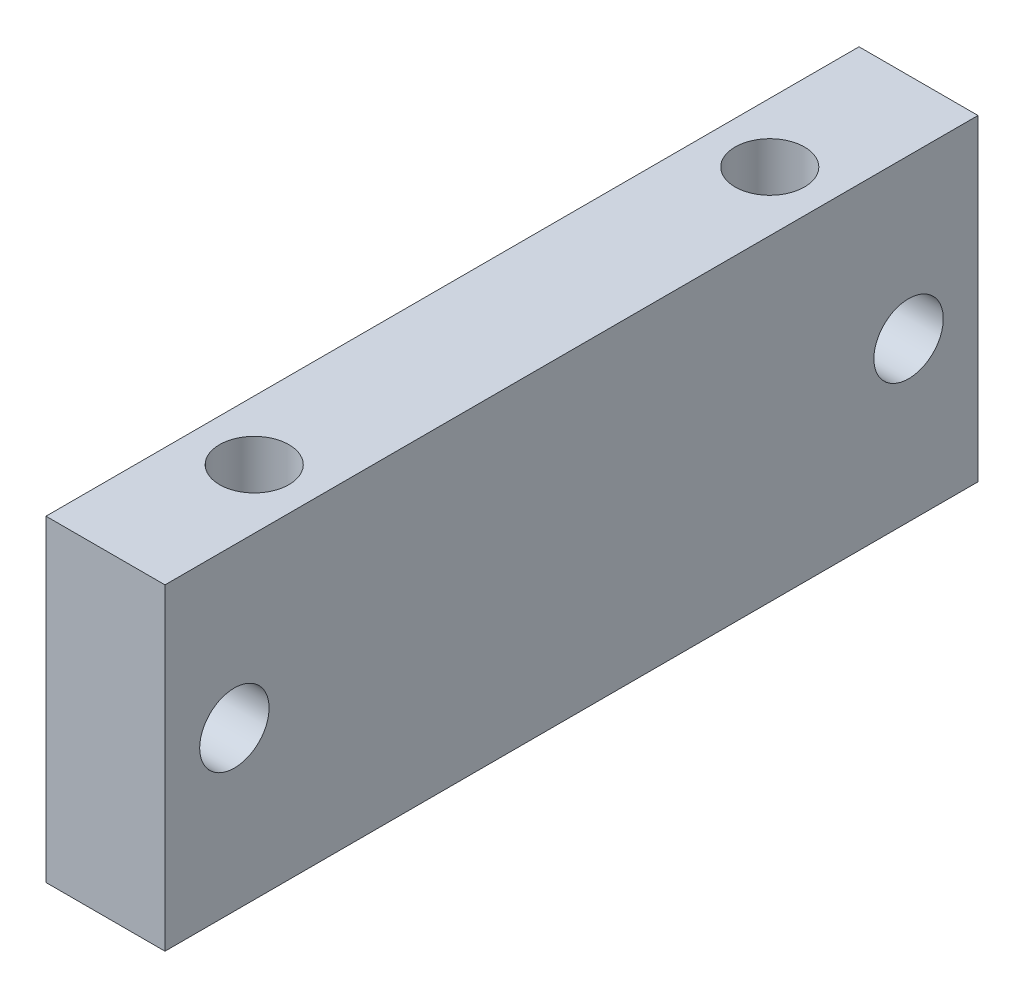
SolidWorks part; units mm, degrees
material "1060 合金"
ref_plane "前视基准面" through (0, 0, 0) normal (0, 0, 1) x (1, 0, 0)
ref_plane "上视基准面" through (0, 0, 0) normal (0, 1, 0) x (1, 0, 0)
ref_plane "右视基准面" through (0, 0, 0) normal (1, 0, 0) x (0, 0, -1)
other "Configuration Table"
sketch "草图1" plane through (0, 0, 0) normal (0, 1, 0) x (1, 0, 0)
  line L1 (-3, -20.5) -> (3, -20.5)
  line L2 (-3, -20.5) -> (-3, 20.5)
  line L3 (-3, 20.5) -> (3, 20.5)
  line L4 (3, -20.5) -> (3, 20.5)
  line L5 (-3, -20.5) -> (3, 20.5) construction
  line L6 (-3, 20.5) -> (3, -20.5) construction
  point P0 (0, 0)
  dimension "D1" = 6
  dimension "D2" = 41
extrude "凸台-拉伸1" add sketch "草图1" along normal blind 16
sketch "草图2" plane through (0, 16, 0) normal (0, 1, 0) x (1, 0, 0)
  line L0 (0, 20.5) -> (0, -20.5) construction
  line L1 (3, 20.5) -> (-3, 20.5) construction
  line L2 (-3, -20.5) -> (3, -20.5) construction
  circle A0 centre (0, 13) radius 1.75
  circle A1 centre (0, -13) radius 1.75
  dimension "D1" = 3.5
  dimension "D2" = 3.5
  dimension "D3" = 13
  dimension "D4" = 13
extrude "切除-拉伸1" cut sketch "草图2" against normal through all
sketch "草图3" plane through (-3, 0, 0) normal (-1, 0, 0) x (0, 0, 1)
  line L0 (-20.5, 8) -> (20.5, 8) construction
  line L1 (-20.5, 16) -> (-20.5, 0) construction
  line L2 (20.5, 16) -> (20.5, 0) construction
  circle A0 centre (-17, 8) radius 1.75
  circle A1 centre (17, 8) radius 1.75
  dimension "D1" = 3.5
  dimension "D2" = 3.5
  dimension "D3" = 17
  dimension "D4" = 17
extrude "切除-拉伸2" cut sketch "草图3" against normal through all
